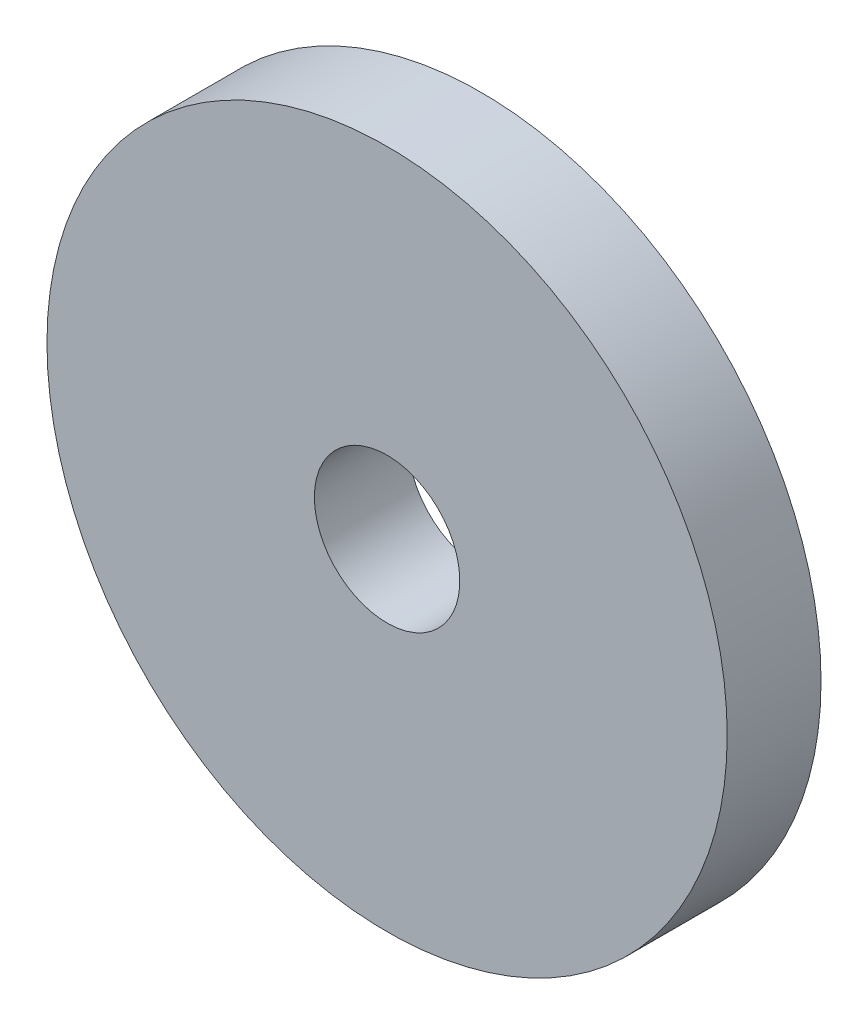
SolidWorks part; units mm, degrees
ref_plane "Front Plane" through (0, 0, 0) normal (0, 0, 1) x (1, 0, 0)
ref_plane "Top Plane" through (0, 0, 0) normal (0, 1, 0) x (1, 0, 0)
ref_plane "Right Plane" through (0, 0, 0) normal (1, 0, 0) x (0, 0, -1)
sketch "Sketch1" plane through (0, 0, 0) normal (0, 0, 1) x (1, 0, 0)
  circle A0 centre (0, 0) radius 7.25
extrude "Boss-Extrude1" add sketch "Sketch1" along normal blind 2
sketch "Sketch2" plane through (0, 0, 0) normal (0, 0, -1) x (-1, 0, 0)
  circle A0 centre (0, 0) radius 1.55
extrude "Cut-Extrude1" cut sketch "Sketch2" against normal blind 2 contours A0
